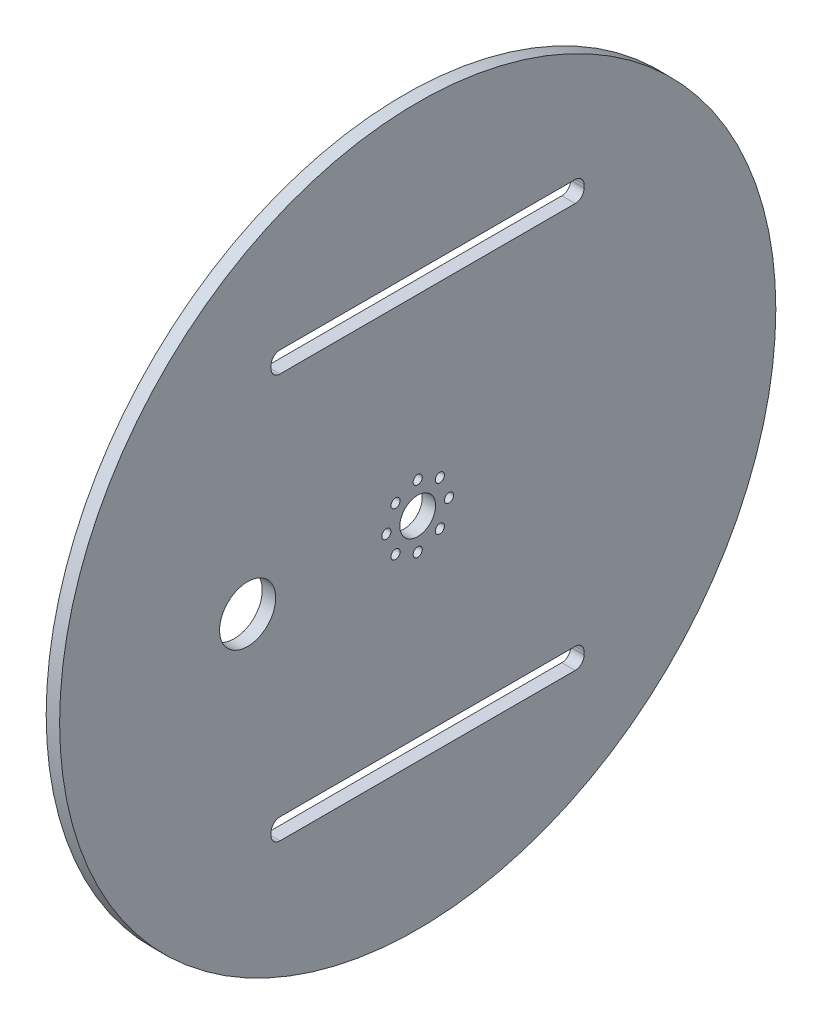
SolidWorks part; units mm, degrees
ref_plane "正面" through (0, 0, 0) normal (0, 0, 1) x (1, 0, 0)
ref_plane "平面" through (0, 0, 0) normal (0, 1, 0) x (1, 0, 0)
ref_plane "右側面" through (0, 0, 0) normal (1, 0, 0) x (0, 0, -1)
sketch "ｽｹｯﾁ1" plane through (0, 0, 0) normal (1, 0, 0) x (0, 0, -1)
  line L0 (-30.7554, 42.8371) -> (35.175, 42.8371)
  line L1 (-32.7554, 44.8371) -> (-32.7554, 45.4891)
  line L2 (-30.7554, 47.4891) -> (35.175, 47.4891)
  line L3 (37.175, 45.4891) -> (37.175, 44.8371)
  line L4 (37.175, -45.4891) -> (37.175, -44.8371)
  line L5 (-30.7554, -47.4891) -> (35.175, -47.4891)
  line L6 (-32.7554, -44.8371) -> (-32.7554, -45.4891)
  line L7 (-30.7554, -42.8371) -> (35.175, -42.8371)
  circle A1 centre (0, 0) radius 4
  circle A2 centre (4.9497, 4.9497) radius 1.02
  circle A3 centre (7, 0) radius 1.02
  circle A4 centre (4.9497, -4.9497) radius 1.02
  circle A5 centre (0, -7) radius 1.02
  circle A6 centre (-4.9497, -4.9497) radius 1.02
  circle A7 centre (-7, 0) radius 1.02
  circle A8 centre (-4.9497, 4.9497) radius 1.02
  circle A9 centre (0, 7) radius 1.02
  circle A10 centre (-38, 0) radius 6.27
  circle A11 centre (0, 0) radius 80
  arc A12 (-32.7554, 44.8371) -> (-30.7554, 42.8371) centre (-30.7554, 44.8371) ccw
  arc A13 (37.175, 44.8371) -> (35.175, 42.8371) centre (35.175, 44.8371) cw
  arc A14 (35.175, 47.4891) -> (37.175, 45.4891) centre (35.175, 45.4891) cw
  arc A15 (-30.7554, 47.4891) -> (-32.7554, 45.4891) centre (-30.7554, 45.4891) ccw
  arc A16 (-30.7554, -47.4891) -> (-32.7554, -45.4891) centre (-30.7554, -45.4891) cw
  arc A17 (35.175, -47.4891) -> (37.175, -45.4891) centre (35.175, -45.4891) ccw
  arc A18 (37.175, -44.8371) -> (35.175, -42.8371) centre (35.175, -44.8371) ccw
  arc A19 (-32.7554, -44.8371) -> (-30.7554, -42.8371) centre (-30.7554, -44.8371) cw
extrude "ﾎﾞｽ - 押し出し1" add sketch "ｽｹｯﾁ1" along normal blind 3
